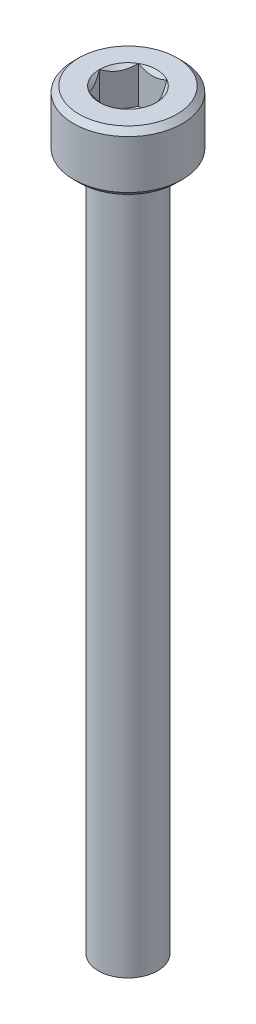
SolidWorks part; units mm, degrees
ref_plane "Front" through (0, 0, 0) normal (0, 0, 1) x (1, 0, 0)
ref_plane "Top" through (0, 0, 0) normal (0, 1, 0) x (1, 0, 0)
ref_plane "Right" through (0, 0, 0) normal (1, 0, 0) x (0, 0, -1)
sketch "Sketch1" plane through (0, 0, 0) normal (0, 1, 0) x (1, 0, 0)
  circle A0 centre (0, 0) radius 2.75
  dimension "D1" = 5.5
extrude "Boss-Extrude1" add sketch "Sketch1" along normal blind 3
sketch "Sketch2" plane through (0, 3, 0) normal (0, 1, 0) x (1, 0, 0)
  line L1 (0.7217, 1.25) -> (-0.7217, 1.25)
  line L2 (-0.7217, 1.25) -> (-1.4434, 0)
  line L3 (-1.4434, 0) -> (-0.7217, -1.25)
  line L4 (-0.7217, -1.25) -> (0.7217, -1.25)
  line L5 (0.7217, -1.25) -> (1.4434, 0)
  line L6 (1.4434, 0) -> (0.7217, 1.25)
  circle A0 centre (0, 0) radius 1.25 construction
  point P10 (0, 1.25)
  dimension "D1" = 2.5
extrude "Cut-Extrude1" cut sketch "Sketch2" against normal blind 1.88
sketch "Sketch5" plane through (0, 3, 0) normal (0, 1, 0) x (1, 0, 0)
  circle A0 centre (0, 0) radius 1.4434
extrude "Cut-Extrude2" cut sketch "Sketch5" against normal through all draft 45
chamfer "Chamfer1" distance 0.275 angle 45 2 edges at (0, 0, 2.75) (0, 3, 2.75)
sketch "草图1" plane through (0, 0, 0) normal (0, -1, 0) x (-1, 0, 0)
  circle A0 centre (0, 0) radius 1.5
  dimension "D1" = 3
extrude "凸台-拉伸1" add sketch "草图1" along normal blind 35
